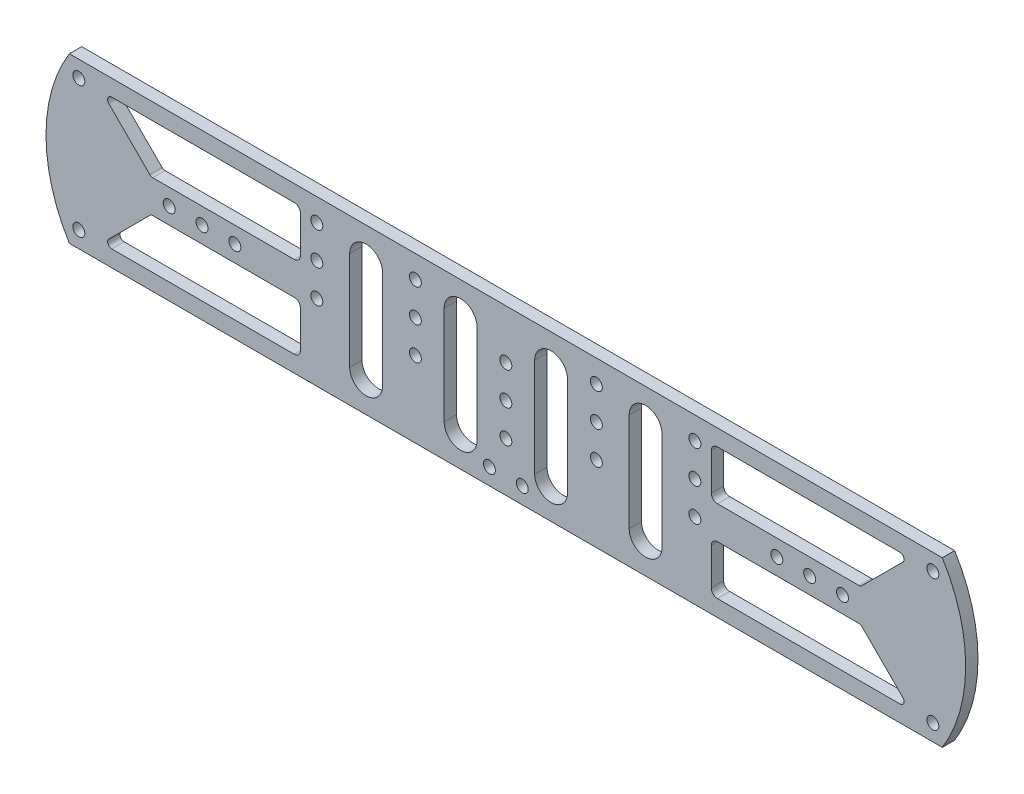
SolidWorks part; units mm, degrees
material "1060 Alloy"
ref_plane "Front Plane" through (0, 0, 0) normal (0, 0, 1) x (1, 0, 0)
ref_plane "Top Plane" through (0, 0, 0) normal (0, 1, 0) x (1, 0, 0)
ref_plane "Right Plane" through (0, 0, 0) normal (1, 0, 0) x (0, 0, -1)
sketch "Sketch1" plane through (0, 0, 0) normal (0, 0, 1) x (1, 0, 0)
  line L0 (-168.7687, 0) -> (168.7687, 0)
  line L1 (-177.8, 0) -> (-177.8, 63.5) construction
  line L2 (-168.7687, 63.5) -> (168.7687, 63.5)
  line L3 (177.8, 63.5) -> (177.8, 0) construction
  line L4 (-177.8, 31.75) -> (177.8, 31.75) construction
  line L5 (0, 0) -> (0, 63.5) construction
  circle A0 centre (-117.475, 31.75) radius 41.275 construction
  circle A1 centre (117.475, 31.75) radius 41.275 construction
  arc A2 (-168.7687, 63.5) -> (-168.7687, 0) centre (-117.475, 31.75) ccw
  arc A3 (168.7687, 0) -> (168.7687, 63.5) centre (117.475, 31.75) ccw
  circle A4 centre (-117.475, 31.75) radius 2.3114
  circle A5 centre (117.475, 31.75) radius 2.3114
  circle A6 centre (-130.175, 31.75) radius 2.3114
  circle A7 centre (-104.775, 31.75) radius 2.3114
  circle A8 centre (104.775, 31.75) radius 2.3114
  circle A9 centre (130.175, 31.75) radius 2.3114
  circle A10 centre (-165.1, 57.15) radius 2.3114
  circle A11 centre (-165.1, 6.35) radius 2.3114
  circle A12 centre (165.1, 6.35) radius 2.3114
  circle A13 centre (165.1, 57.15) radius 2.3114
  point P27 (-165.1, 57.15)
  dimension "D3" = 82.55
  dimension "D6" = 4.6228
  dimension "D13" = 4.6228
  dimension "D1" = 355.6
  dimension "D2" = 63.5
  dimension "D4" = 60.325
  dimension "D5" = 60.325
  dimension "D7" = 12.7
  dimension "D8" = 12.7
  dimension "D9" = 12.7
  dimension "D10" = 12.7
  dimension "D11" = 6.35
  dimension "D12" = 12.7
extrude "Boss-Extrude1" add sketch "Sketch1" along normal blind 4.7625
sketch "Sketch2" plane through (0, 0, 0) normal (0, 0, 1) x (1, 0, 0)
  line L0 (168.7687, 63.5) -> (-168.7687, 63.5) construction
  line L1 (-73.0887, 70.7723) -> (-73.0887, 13.3683) construction
  line L2 (-89.5987, 70.7723) -> (-56.5787, 70.7723) construction
  line L3 (-89.5987, 70.7723) -> (-89.5987, 13.3683) construction
  line L4 (-89.5987, 13.3683) -> (-56.5787, 13.3683) construction
  line L5 (-56.5787, 70.7723) -> (-56.5787, 13.3683) construction
  line L6 (34.9887, 70.7723) -> (34.9887, 13.3683) construction
  line L7 (18.4787, 70.7723) -> (51.4987, 70.7723) construction
  line L8 (18.4787, 70.7723) -> (18.4787, 13.3683) construction
  line L9 (18.4787, 13.3683) -> (51.4987, 13.3683) construction
  line L10 (51.4987, 70.7723) -> (51.4987, 13.3683) construction
  line L11 (-34.9887, 70.7723) -> (-34.9887, 13.3683) construction
  line L12 (-51.4987, 70.7723) -> (-18.4787, 70.7723) construction
  line L13 (-51.4987, 70.7723) -> (-51.4987, 13.3683) construction
  line L14 (-51.4987, 13.3683) -> (-18.4787, 13.3683) construction
  line L15 (-18.4787, 70.7723) -> (-18.4787, 13.3683) construction
  line L16 (73.0887, 70.7723) -> (73.0887, 13.3683) construction
  line L17 (56.5787, 70.7723) -> (89.5987, 70.7723) construction
  line L18 (56.5787, 70.7723) -> (56.5787, 13.3683) construction
  line L19 (56.5787, 13.3683) -> (89.5987, 13.3683) construction
  line L20 (89.5987, 70.7723) -> (89.5987, 13.3683) construction
  line L21 (0, 0) -> (0, 6.35) construction
  line L22 (-6.35, 6.35) -> (6.35, 6.35) construction
  line L23 (-168.7687, 0) -> (168.7687, 0) construction
  circle A0 centre (-117.475, 31.75) radius 41.275 construction
  circle A1 centre (117.475, 31.75) radius 41.275 construction
  circle A2 centre (-117.475, 31.75) radius 25.4 construction
  circle A3 centre (-73.0887, 29.3703) radius 19.05 construction
  circle A4 centre (34.9887, 29.3703) radius 19.05 construction
  circle A5 centre (0, 44.45) radius 19.05 construction
  circle A6 centre (-34.9887, 29.3703) radius 19.05 construction
  circle A7 centre (117.475, 31.75) radius 25.4 construction
  circle A8 centre (73.0887, 29.3703) radius 19.05 construction
  point P22 (-73.0887, 42.0703)
  point P23 (-73.0887, 54.7703)
  point P24 (-73.0887, 29.3703)
  point P35 (34.9887, 42.0703)
  point P36 (34.9887, 54.7703)
  point P37 (34.9887, 29.3703)
  point P45 (-34.9887, 42.0703)
  point P46 (-34.9887, 54.7703)
  point P47 (-34.9887, 29.3703)
  point P48 (0, 6.35)
  point P57 (73.0887, 42.0703)
  point P58 (73.0887, 54.7703)
  point P59 (73.0887, 29.3703)
  dimension "D1" = 82.55
  dimension "D2" = 50.8
  dimension "D3" = 38.1
  dimension "D4" = 57.404
  dimension "D5" = 33.02
  dimension "D6" = 12.7
  dimension "D7" = 12.7
  dimension "D8" = 57.404
  dimension "D9" = 33.02
  dimension "D10" = 12.7
  dimension "D11" = 12.7
  dimension "D12" = 57.404
  dimension "D13" = 33.02
  dimension "D14" = 12.7
  dimension "D15" = 12.7
  dimension "D16" = 57.404
  dimension "D17" = 33.02
  dimension "D18" = 12.7
  dimension "D19" = 12.7
  dimension "D20" = 6.35
  dimension "D21" = 12.7
sketch "Sketch3" plane through (0, 0, 4.7625) normal (0, 0, 1) x (1, 0, 0)
  line L0 (-73.0887, 70.7723) -> (-73.0887, 13.3683) construction
  point P0 (-73.0887, 54.7703)
  point P1 (-73.0887, 42.0703)
  point P3 (-73.0887, 29.3703)
  point P6 (-34.9887, 29.3703)
  point P8 (-34.9887, 42.0703)
  point P10 (-34.9887, 54.7703)
  point P12 (34.9887, 54.7703)
  point P14 (34.9887, 42.0703)
  point P16 (34.9887, 29.3703)
  point P18 (73.0887, 29.3703)
  point P20 (73.0887, 42.0703)
  point P22 (73.0887, 54.7703)
  point P24 (0, 44.45)
  point P26 (0, 31.75)
  point P28 (0, 19.05)
  point P29 (-6.35, 6.35)
  point P32 (6.35, 6.35)
  dimension "D1" = 12.7
  dimension "D2" = 12.7
hole_wizard "#14 (0.182) Diameter Hole1" positions "Sketch3" profile "Sketch4" hole size "#14" standard "ANSI Inch" end condition through all
sketch "Sketch4" plane through (-73.0887, 54.7703, 4.7625) normal (1, 0, 0) x (0, -1, 0)
  line L0 (0, 0) -> (0, 4.7625)
  line L1 (0, 4.7625) -> (2.3114, 4.7625)
  line L2 (2.3114, 4.7625) -> (2.3114, 0)
  line L5 (2.3114, 0) -> (0, 0)
  line L11 (0, -6.35) -> (0, 107.95) construction
  dimension "Thru Hole Dia." = 4.6228
  dimension "Thru Hole Depth" = 4.7625
sketch "Sketch7" plane through (0, 0, 4.7625) normal (0, 0, 1) x (1, 0, 0)
  line L0 (-153.5218, 54.4417) -> (-137.6448, 38.5647)
  line L1 (-136.5229, 38.1) -> (-81.8185, 38.1)
  line L2 (-79.4387, 40.4797) -> (-79.4387, 54.7703)
  line L3 (-81.8185, 57.15) -> (-152.4, 57.15)
  line L4 (168.7687, 63.5) -> (-168.7687, 63.5) construction
  line L5 (0, 44.45) -> (0, 0) construction
  line L6 (-24.2337, 31.75) -> (25.1961, 31.75) construction
  line L7 (81.8185, 57.15) -> (152.4, 57.15)
  line L8 (79.4387, 40.4797) -> (79.4387, 54.7703)
  line L9 (136.5229, 38.1) -> (81.8185, 38.1)
  line L10 (153.5218, 54.4417) -> (137.6448, 38.5647)
  line L11 (-81.8185, 6.35) -> (-152.4, 6.35)
  line L12 (-79.4387, 23.0203) -> (-79.4387, 8.7297)
  line L13 (-136.5229, 25.4) -> (-81.8185, 25.4)
  line L14 (-153.5218, 9.0583) -> (-137.6448, 24.9353)
  line L15 (79.4387, 23.0203) -> (79.4387, 8.7297)
  line L16 (136.5229, 25.4) -> (81.8185, 25.4)
  line L17 (153.5218, 9.0583) -> (137.6448, 24.9353)
  line L18 (81.8185, 6.35) -> (152.4, 6.35)
  arc A0 (-137.6448, 38.5647) -> (-136.5229, 38.1) centre (-136.5229, 39.6865) ccw
  arc A1 (-81.8185, 38.1) -> (-79.4387, 40.4797) centre (-81.8185, 40.4797) ccw
  arc A2 (-79.4387, 54.7703) -> (-81.8185, 57.15) centre (-81.8185, 54.7703) ccw
  arc A3 (-152.4, 57.15) -> (-153.5218, 54.4417) centre (-152.4, 55.5635) ccw
  arc A4 (79.4387, 54.7703) -> (81.8185, 57.15) centre (81.8185, 54.7703) cw
  arc A5 (81.8185, 38.1) -> (79.4387, 40.4797) centre (81.8185, 40.4797) cw
  arc A6 (137.6448, 38.5647) -> (136.5229, 38.1) centre (136.5229, 39.6865) cw
  arc A7 (152.4, 57.15) -> (153.5218, 54.4417) centre (152.4, 55.5635) cw
  arc A8 (-79.4387, 8.7297) -> (-81.8185, 6.35) centre (-81.8185, 8.7297) cw
  arc A9 (-81.8185, 25.4) -> (-79.4387, 23.0203) centre (-81.8185, 23.0203) cw
  arc A10 (-137.6448, 24.9353) -> (-136.5229, 25.4) centre (-136.5229, 23.8135) cw
  arc A11 (-152.4, 6.35) -> (-153.5218, 9.0583) centre (-152.4, 7.9365) cw
  arc A12 (79.4387, 8.7297) -> (81.8185, 6.35) centre (81.8185, 8.7297) ccw
  arc A13 (81.8185, 25.4) -> (79.4387, 23.0203) centre (81.8185, 23.0203) ccw
  arc A14 (137.6448, 24.9353) -> (136.5229, 25.4) centre (136.5229, 23.8135) ccw
  arc A15 (152.4, 6.35) -> (153.5218, 9.0583) centre (152.4, 7.9365) ccw
  point P17 (0, 31.75)
  point P22 (-165.1, 57.15)
  dimension "D1" = 6.35
  dimension "D2" = 6.35
  dimension "D3" = 6.35
  dimension "D4" = 45
  dimension "D5" = 12.7
extrude "WeightCutting_2" cut sketch "Sketch7" against normal through all both and the other way through all
sketch "Sketch8" plane through (0, 0, 4.7625) normal (0, 0, 1) x (1, 0, 0)
  line L0 (-66.7387, 8.7297) -> (-66.7387, 14.2906)
  line L1 (-64.359, 16.6703) -> (-11.9047, 16.6703)
  line L2 (-9.525, 14.2906) -> (-9.525, 8.7297)
  line L3 (-11.9047, 6.35) -> (-64.359, 6.35)
  line L4 (-152.4, 6.35) -> (-81.8185, 6.35) construction
  line L5 (-73.0887, 42.0703) -> (-73.0887, -7.2875) construction
  line L6 (0, 0) -> (0, 66.3994) construction
  line L7 (11.9047, 6.35) -> (64.359, 6.35)
  line L8 (9.525, 14.2906) -> (9.525, 8.7297)
  line L9 (64.359, 16.6703) -> (11.9047, 16.6703)
  line L10 (66.7387, 8.7297) -> (66.7387, 14.2906)
  arc A0 (-66.7387, 14.2906) -> (-64.359, 16.6703) centre (-64.359, 14.2906) cw
  arc A1 (-11.9047, 16.6703) -> (-9.525, 14.2906) centre (-11.9047, 14.2906) cw
  arc A2 (-9.525, 8.7297) -> (-11.9047, 6.35) centre (-11.9047, 8.7297) cw
  arc A3 (-64.359, 6.35) -> (-66.7387, 8.7297) centre (-64.359, 8.7297) cw
  arc A4 (-79.4387, 23.0203) -> (-81.8185, 25.4) centre (-81.8185, 23.0203) ccw construction
  arc A5 (9.525, 8.7297) -> (11.9047, 6.35) centre (11.9047, 8.7297) ccw
  arc A6 (11.9047, 16.6703) -> (9.525, 14.2906) centre (11.9047, 14.2906) ccw
  arc A7 (66.7387, 14.2906) -> (64.359, 16.6703) centre (64.359, 14.2906) ccw
  arc A8 (64.359, 6.35) -> (66.7387, 8.7297) centre (64.359, 8.7297) ccw
  point P14 (-73.0887, 42.0703)
  point P18 (-73.0887, 29.3703)
  dimension "D1" = 6.35
  dimension "D2" = 12.7
  dimension "D3" = 9.525
extrude "WeightCutting_3" [suppressed] cut sketch "Sketch8" against normal through all both and the other way through all
sketch "Sketch9" plane through (0, 0, 4.7625) normal (0, 0, 1) x (1, 0, 0)
  line L0 (-54.0387, 50.8) -> (-54.0387, 12.7) construction
  line L1 (-47.6887, 50.8) -> (-47.6887, 12.7)
  line L2 (-60.3887, 50.8) -> (-60.3887, 12.7)
  line L3 (0, 0) -> (0, 81.4347) construction
  line L4 (-73.0887, 42.0703) -> (-34.9887, 42.0703) construction
  line L5 (168.7687, 63.5) -> (-168.7687, 63.5) construction
  line L6 (-34.9887, 29.3703) -> (0, 29.3703) construction
  line L9 (34.9887, 29.3703) -> (0, 29.3703) construction
  line L12 (34.9887, 42.0703) -> (73.0887, 42.0703) construction
  line L15 (54.0387, 50.8) -> (54.0387, 12.7) construction
  line L16 (60.3887, 50.8) -> (60.3887, 12.7)
  line L17 (47.6887, 50.8) -> (47.6887, 12.7)
  line L18 (17.4944, 50.8) -> (17.4944, 12.7) construction
  line L19 (23.8444, 50.8) -> (23.8444, 12.7)
  line L20 (11.1444, 50.8) -> (11.1444, 12.7)
  line L21 (-17.4944, 50.8) -> (-17.4944, 12.7) construction
  line L22 (-11.1444, 50.8) -> (-11.1444, 12.7)
  line L23 (-23.8444, 50.8) -> (-23.8444, 12.7)
  arc A0 (-47.6887, 50.8) -> (-60.3887, 50.8) centre (-54.0387, 50.8) ccw
  arc A1 (-60.3887, 12.7) -> (-47.6887, 12.7) centre (-54.0387, 12.7) ccw
  arc A9 (60.3887, 50.8) -> (47.6887, 50.8) centre (54.0387, 50.8) ccw
  arc A10 (47.6887, 12.7) -> (60.3887, 12.7) centre (54.0387, 12.7) ccw
  arc A11 (23.8444, 50.8) -> (11.1444, 50.8) centre (17.4944, 50.8) ccw
  arc A12 (11.1444, 12.7) -> (23.8444, 12.7) centre (17.4944, 12.7) ccw
  arc A13 (-11.1444, 50.8) -> (-23.8444, 50.8) centre (-17.4944, 50.8) ccw
  arc A14 (-23.8444, 12.7) -> (-11.1444, 12.7) centre (-17.4944, 12.7) ccw
  point P2 (-54.0387, 31.75)
  point P7 (0, 31.75)
  point P8 (-34.9887, 42.0703)
  point P13 (-73.0887, 42.0703)
  point P18 (-54.0387, 42.0703)
  point P26 (-17.4944, 29.3703)
  point P27 (17.4944, 29.3703)
  point P28 (54.0387, 42.0703)
  point P31 (54.0387, 31.75)
  point P38 (17.4944, 31.75)
  point P45 (-17.4944, 31.75)
  dimension "D1" = 6.35
  dimension "D2" = 12.7
extrude "Cut-Extrude1" cut sketch "Sketch9" against normal through all
